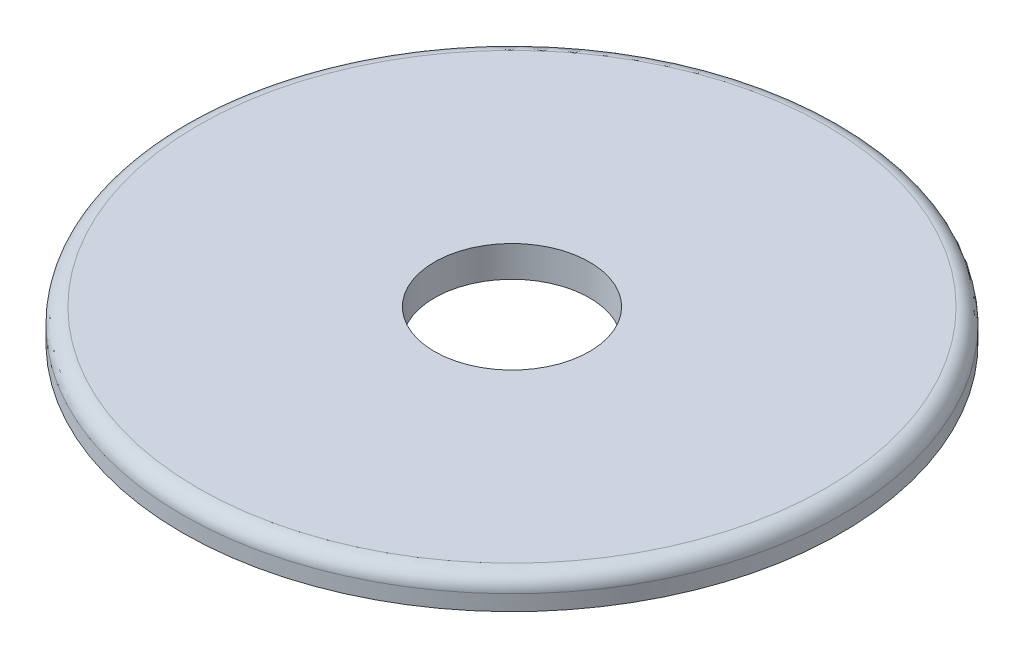
SolidWorks part; units mm, degrees
ref_plane "Front Plane" through (0, 0, 0) normal (0, 0, 1) x (1, 0, 0)
ref_plane "Top Plane" through (0, 0, 0) normal (0, 1, 0) x (1, 0, 0)
ref_plane "Right Plane" through (0, 0, 0) normal (1, 0, 0) x (0, 0, -1)
sketch "Sketch1" plane through (0, 0, 0) normal (0, 1, 0) x (1, 0, 0)
  circle A0 centre (0, 0) radius 5
  circle A1 centre (0, 0) radius 21.25
extrude "Boss-Extrude1" add sketch "Sketch1" along normal blind 2
fillet "Fillet1" radius 1 1 edges at (0, 2, 21.25)
